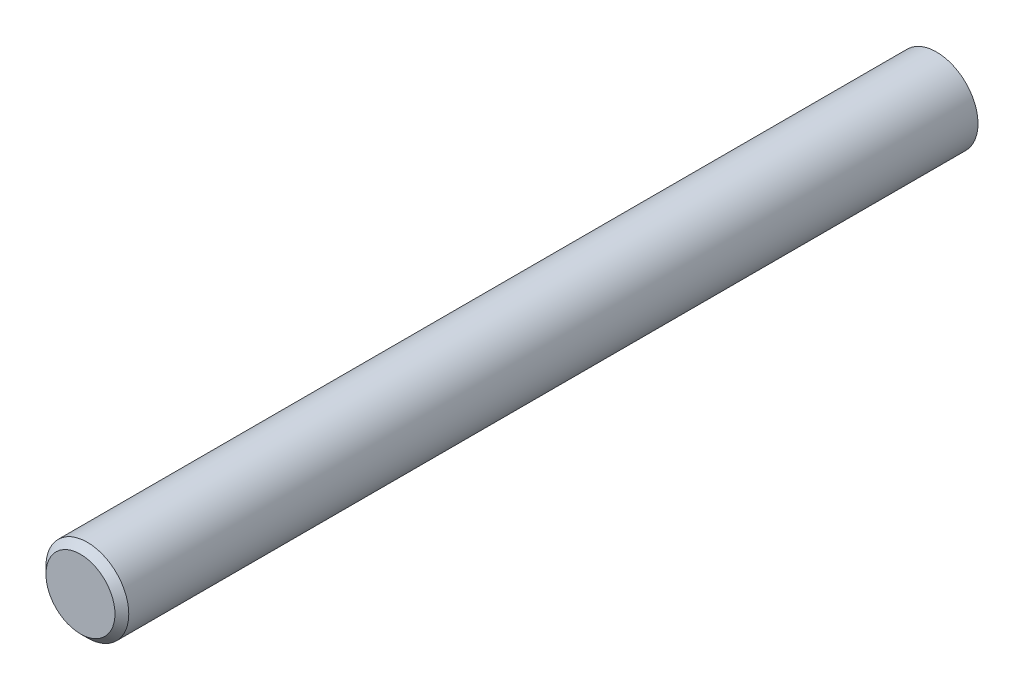
SolidWorks part; units mm, degrees
ref_plane "Plan de face" through (0, 0, 0) normal (0, 0, 1) x (1, 0, 0)
ref_plane "Plan de dessus" through (0, 0, 0) normal (0, 1, 0) x (1, 0, 0)
ref_plane "Plan de droite" through (0, 0, 0) normal (1, 0, 0) x (0, 0, -1)
sketch "Esquisse1" plane through (0, 0, 0) normal (0, 0, 1) x (1, 0, 0)
  circle A0 centre (0, 0) radius 6
  dimension "D1" = 12
extrude "Boss.-Extru.1" add sketch "Esquisse1" along normal blind 124
chamfer "Chanfrein1" distance 1 angle 45 1 edges at (6, 0, 124)
